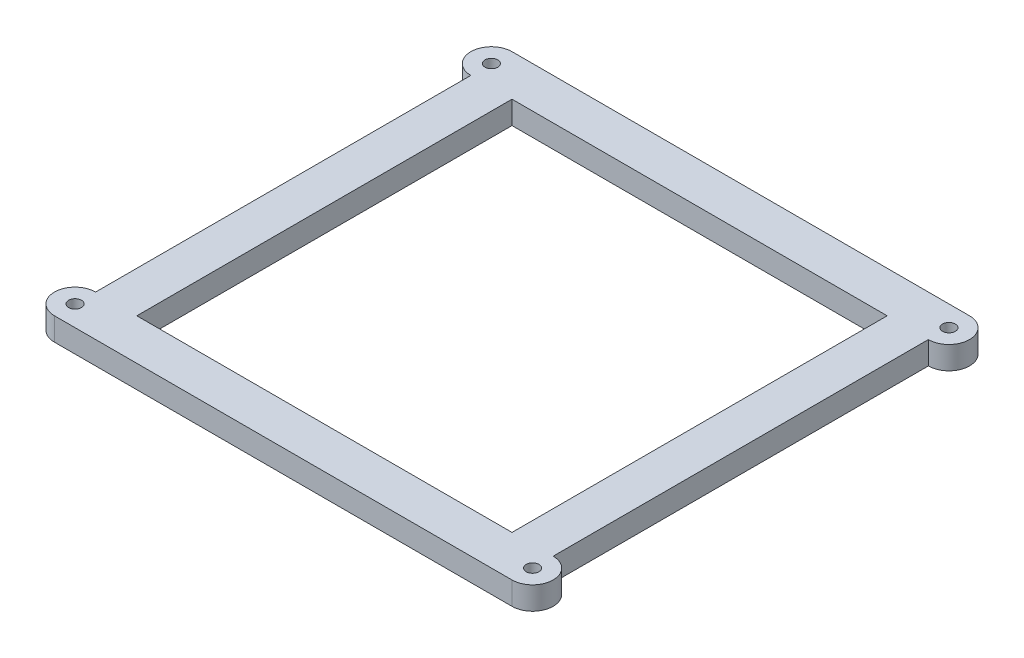
SolidWorks part; units mm, degrees
ref_plane "Front Plane" through (0, 0, 0) normal (0, 0, 1) x (1, 0, 0)
ref_plane "Top Plane" through (0, 0, 0) normal (0, 1, 0) x (1, 0, 0)
ref_plane "Right Plane" through (0, 0, 0) normal (1, 0, 0) x (0, 0, -1)
sketch "Sketch1" plane through (0, 0, 0) normal (0, 1, 0) x (1, 0, 0)
  line L0 (0, 0) -> (63.5, 63.5) construction
  line L1 (0, 0) -> (63.5, 0)
  line L2 (0, 5.715) -> (0, 57.785)
  line L3 (0, 63.5) -> (63.5, 63.5)
  line L4 (63.5, 5.715) -> (63.5, 57.785)
  line L5 (0, 63.5) -> (63.5, 0) construction
  line L6 (5.715, 57.785) -> (5.715, 63.5) construction
  line L7 (5.715, 5.715) -> (57.785, 5.715)
  line L8 (5.715, 5.715) -> (5.715, 57.785)
  line L9 (5.715, 57.785) -> (57.785, 57.785)
  line L10 (57.785, 5.715) -> (57.785, 57.785)
  line L11 (5.715, 5.715) -> (57.785, 57.785) construction
  line L12 (5.715, 57.785) -> (57.785, 5.715) construction
  line L13 (57.785, 57.785) -> (57.785, 63.5) construction
  line L14 (0, 60.6425) -> (63.5, 60.6425) construction
  line L15 (63.5, 57.785) -> (63.5, 60.6425) construction
  line L16 (63.5, 60.6425) -> (63.5, 63.5) construction
  line L17 (0, 60.6425) -> (0, 63.5) construction
  line L18 (0, 57.785) -> (0, 60.6425) construction
  line L19 (0, 31.75) -> (63.5, 31.75) construction
  line L20 (0, 2.8575) -> (0, 0) construction
  line L21 (0, 5.715) -> (0, 2.8575) construction
  line L22 (63.5, 2.8575) -> (63.5, 0) construction
  line L23 (63.5, 5.715) -> (63.5, 2.8575) construction
  line L24 (63.5, 0) -> (63.5, 2.8575) construction
  line L25 (63.5, 2.8575) -> (63.5, 5.715) construction
  line L26 (0, 0) -> (0, 2.8575) construction
  line L27 (0, 2.8575) -> (0, 5.715) construction
  arc A0 (63.5, 63.5) -> (63.5, 57.785) centre (63.5, 60.6425) cw
  arc A1 (0, 63.5) -> (0, 57.785) centre (0, 60.6425) ccw
  arc A2 (63.5, 0) -> (63.5, 5.715) centre (63.5, 2.8575) ccw
  arc A3 (0, 0) -> (0, 5.715) centre (0, 2.8575) cw
  point P5 (31.75, 31.75)
  point P7 (31.75, 31.75)
  point P15 (57.785, 60.6425)
  point P16 (5.715, 60.6425)
  dimension "D1" = 63.5
  dimension "D2" = 52.07
extrude "Boss-Extrude1" add sketch "Sketch1" along normal blind 3.175
hole_wizard "M2 Clearance Hole1" positions "Sketch4" profile "Sketch5" hole size "M2" standard "ANSI Metric"
sketch "Sketch4" plane through (0, 0, 0) normal (0, -1, 0) x (-1, 0, 0)
  point P0 (-63.5, 60.6425)
  point P3 (0, 60.6425)
  point P6 (0, 2.8575)
  point P9 (-63.5, 2.8575)
sketch "Sketch5" plane through (63.5, 0, -60.6425) normal (1, 0, 0) x (0, 0, -1)
  line L0 (0, 0) -> (0, 3.7089)
  line L1 (0, 3.7089) -> (1.1, 3.048)
  line L2 (1.1, 3.048) -> (1.1, 0)
  line L5 (1.1, 0) -> (0, 0)
  line L10 (0, 3.7089) -> (-1.1, 3.048) construction
  line L11 (0, -6.35) -> (0, 107.95) construction
  dimension "Hole Dia." = 2.2
  dimension "Hole Depth" = 3.048
  dimension "Drill Angle" = 118
